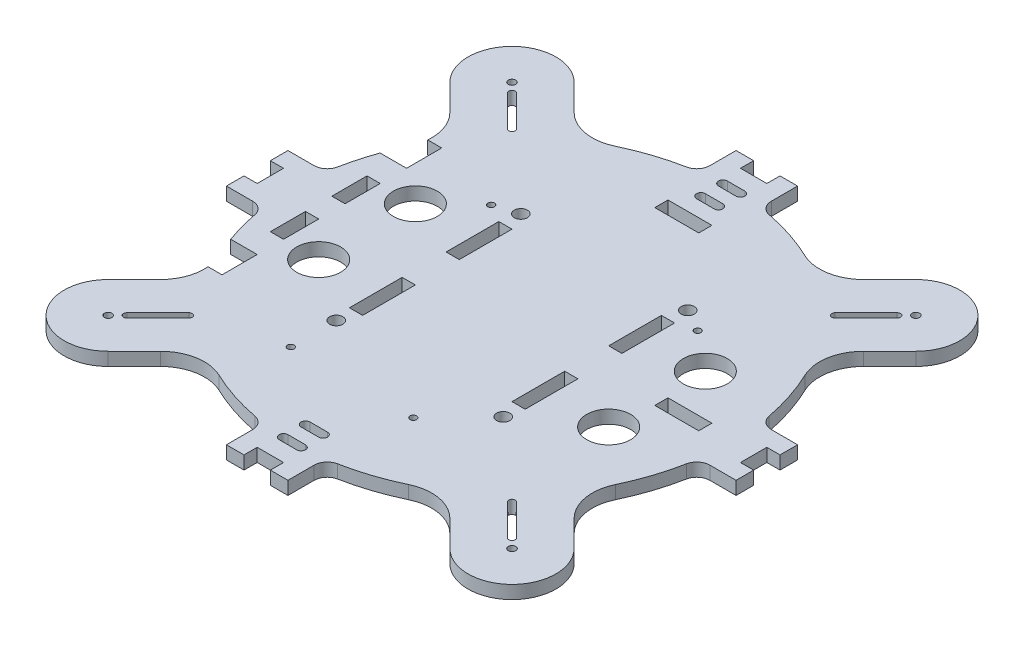
SolidWorks part; units mm, degrees
ref_plane "Plan de face" through (0, 0, 0) normal (0, 0, 1) x (1, 0, 0)
ref_plane "Plan de dessus" through (0, 0, 0) normal (0, 1, 0) x (1, 0, 0)
ref_plane "Plan de droite" through (0, 0, 0) normal (1, 0, 0) x (0, 0, -1)
sketch "Esquisse1" plane through (0, 0, 0) normal (0, 1, 0) x (1, 0, 0)
  line L0 (-45.9619, -45.9619) -> (0, 0) construction
  line L1 (0, 0) -> (-75, 0) construction
  line L2 (-45.9619, -45.9619) -> (-53.033, -53.033) construction
  line L3 (0, 0) -> (0, 75) construction
  line L4 (-38.8909, -53.033) -> (-27.5699, -41.7121)
  line L5 (-53.033, -38.8909) -> (-41.7121, -27.5699)
  line L6 (-38.8909, 53.033) -> (-27.5699, 41.7121)
  line L7 (-41.7121, 27.5699) -> (-53.033, 38.8909)
  line L8 (0, 0) -> (-45.9619, 45.9619) construction
  line L9 (0, 0) -> (45.9619, 45.9619) construction
  line L10 (0, 0) -> (45.9619, -45.9619) construction
  line L11 (27.5699, 41.7121) -> (38.8909, 53.033)
  line L12 (41.7121, 27.5699) -> (53.033, 38.8909)
  line L13 (27.5699, -41.7121) -> (38.8909, -53.033)
  line L14 (41.7121, -27.5699) -> (53.033, -38.8909)
  line L15 (-20, 17) -> (-17, 17)
  line L18 (-20, 17) -> (-20, 5)
  line L21 (-20, 5) -> (-17, 5)
  line L24 (-17, 17) -> (-17, 5)
  line L27 (-19, -21) -> (19, -21) construction
  line L28 (-19, -21) -> (-19, 21) construction
  line L29 (-19, 21) -> (19, 21) construction
  line L30 (19, -21) -> (19, 21) construction
  line L31 (-19, -21) -> (19, 21) construction
  line L32 (-19, 21) -> (19, -21) construction
  line L33 (20, 5) -> (17, 5)
  line L34 (17, 17) -> (17, 5)
  line L35 (20, 17) -> (17, 17)
  line L36 (20, 17) -> (20, 5)
  line L37 (-17, 5) -> (-17, -5) construction
  line L38 (17, -17) -> (20, -17)
  line L39 (-17, -5) -> (-20, -5)
  line L40 (-17, -5) -> (-17, -17)
  line L41 (-17, -17) -> (-20, -17)
  line L42 (-20, -5) -> (-20, -17)
  line L43 (20, -5) -> (20, -17)
  line L44 (17, -5) -> (20, -5)
  line L45 (17, -5) -> (17, -17)
  line L46 (-43.8406, -43.8406) -> (-36.7696, -36.7696) construction
  line L47 (-24.15, 19.4) -> (24.15, 19.4) construction
  line L48 (-24.15, 19.4) -> (-24.15, -31.4) construction
  line L49 (-24.15, -31.4) -> (24.15, -31.4) construction
  line L50 (24.15, 19.4) -> (24.15, -31.4) construction
  line L51 (33, -11) -> (-33, -11) construction
  line L52 (33, -11) -> (33, 11) construction
  line L53 (33, 11) -> (-33, 11) construction
  line L54 (-33, -11) -> (-33, 11) construction
  line L55 (33, -11) -> (-33, 11) construction
  line L56 (33, 11) -> (-33, -11) construction
  line L57 (-44.371, -43.3103) -> (-37.2999, -36.2392)
  line L58 (-43.3103, -44.371) -> (-36.2392, -37.2999)
  line L59 (-43.8406, 43.8406) -> (-36.7696, 36.7696) construction
  line L60 (-43.3103, 44.371) -> (-36.2392, 37.2999)
  line L61 (-44.371, 43.3103) -> (-37.2999, 36.2392)
  line L62 (-24.15, 0) -> (24.15, 0) construction
  line L63 (43.8406, 43.8406) -> (36.7696, 36.7696) construction
  line L64 (44.371, 43.3103) -> (37.2999, 36.2392)
  line L65 (43.3103, 44.371) -> (36.2392, 37.2999)
  line L66 (43.8406, -43.8406) -> (36.7696, -36.7696) construction
  line L67 (43.3103, -44.371) -> (36.2392, -37.2999)
  line L68 (44.371, -43.3103) -> (37.2999, -36.2392)
  line L69 (-2, -45) -> (2, -45) construction
  line L70 (-2, -44) -> (2, -44)
  line L71 (-2, -46) -> (2, -46)
  line L72 (-2, -50) -> (2, -50) construction
  line L73 (-2, -49) -> (2, -49)
  line L74 (-2, -51) -> (2, -51)
  line L75 (0, 0) -> (0, -75) construction
  line L76 (-7, -58) -> (-3, -58)
  line L77 (7, -58) -> (7, -49.5076)
  line L78 (-7, -58) -> (-7, -49.5076)
  line L79 (-3, -58) -> (-3, -55)
  line L80 (-3, -55) -> (3, -55)
  line L81 (3, -55) -> (3, -58)
  line L82 (3, -58) -> (7, -58)
  line L83 (-58, -7) -> (-49.5076, -7)
  line L84 (-58, -3) -> (-58, -7)
  line L85 (-55, -3) -> (-58, -3)
  line L86 (-55, 3) -> (-55, -3)
  line L87 (-58, 3) -> (-55, 3)
  line L88 (-58, 7) -> (-58, 3)
  line L89 (-58, 7) -> (-49.5076, 7)
  line L90 (-7, 58) -> (-7, 49.5076)
  line L91 (-3, 58) -> (-7, 58)
  line L92 (-3, 55) -> (-3, 58)
  line L93 (3, 55) -> (-3, 55)
  line L94 (3, 58) -> (3, 55)
  line L95 (7, 58) -> (3, 58)
  line L96 (7, 58) -> (7, 49.5076)
  line L97 (58, 7) -> (49.5076, 7)
  line L98 (58, 3) -> (58, 7)
  line L99 (55, 3) -> (58, 3)
  line L100 (55, -3) -> (55, 3)
  line L101 (58, -3) -> (55, -3)
  line L102 (58, -7) -> (58, -3)
  line L103 (58, -7) -> (49.5076, -7)
  line L104 (-2, 50) -> (2, 50) construction
  line L105 (-2, 49) -> (2, 49)
  line L106 (-2, 51) -> (2, 51)
  line L107 (-2, 45) -> (2, 45) construction
  line L108 (-2, 44) -> (2, 44)
  line L109 (-2, 46) -> (2, 46)
  line L110 (0, 0) -> (75, 0) construction
  line L111 (34, 1.5) -> (44, 1.5)
  line L112 (34, 1.5) -> (34, -1.5)
  line L113 (34, -1.5) -> (44, -1.5)
  line L114 (44, 1.5) -> (44, -1.5)
  line L116 (-5, 40.5) -> (5, 40.5)
  line L117 (-5, 40.5) -> (-5, 37.5)
  line L118 (-5, 37.5) -> (5, 37.5)
  line L119 (5, 40.5) -> (5, 37.5)
  circle A0 centre (0, 0) radius 75 construction
  circle A1 centre (-45.9619, -45.9619) radius 0.85
  circle A2 centre (-45.9619, 45.9619) radius 0.85
  circle A3 centre (45.9619, 45.9619) radius 0.85
  circle A4 centre (45.9619, -45.9619) radius 0.85
  arc A9 (-27.5699, -41.7121) -> (-7, -49.5076) centre (0, 0) ccw
  arc A10 (-53.033, -38.8909) -> (-38.8909, -53.033) centre (-45.9619, -45.9619) ccw
  arc A11 (38.8909, -53.033) -> (53.033, -38.8909) centre (45.9619, -45.9619) ccw
  arc A12 (53.033, 38.8909) -> (38.8909, 53.033) centre (45.9619, 45.9619) ccw
  arc A13 (-38.8909, 53.033) -> (-53.033, 38.8909) centre (-45.9619, 45.9619) ccw
  arc A14 (-41.7121, 27.5699) -> (-49.5076, 7) centre (0, 0) ccw
  arc A15 (27.5699, 41.7121) -> (7, 49.5076) centre (0, 0) ccw
  arc A16 (41.7121, -27.5699) -> (49.5076, -7) centre (0, 0) ccw
  circle A25 centre (-19, 21) radius 1.5
  circle A26 centre (19, 21) radius 1.5
  circle A27 centre (19, -21) radius 1.5
  circle A28 centre (-19, -21) radius 1.5
  circle A29 centre (24.15, 18.1) radius 0.75
  circle A30 centre (-24.15, 19.4) radius 0.75
  circle A31 centre (-18.95, -31.4) radius 0.75
  circle A32 centre (8.95, -31.4) radius 0.75
  circle A33 centre (-33, 11) radius 5
  circle A34 centre (33, 11) radius 5
  circle A35 centre (33, -11) radius 5
  circle A36 centre (-33, -11) radius 5
  arc A37 (-44.371, -43.3103) -> (-43.3103, -44.371) centre (-43.8406, -43.8406) ccw
  arc A38 (-36.2392, -37.2999) -> (-37.2999, -36.2392) centre (-36.7696, -36.7696) ccw
  arc A39 (-43.3103, 44.371) -> (-44.371, 43.3103) centre (-43.8406, 43.8406) ccw
  arc A40 (-37.2999, 36.2392) -> (-36.2392, 37.2999) centre (-36.7696, 36.7696) ccw
  arc A41 (44.371, 43.3103) -> (43.3103, 44.371) centre (43.8406, 43.8406) ccw
  arc A42 (36.2392, 37.2999) -> (37.2999, 36.2392) centre (36.7696, 36.7696) ccw
  arc A43 (43.3103, -44.371) -> (44.371, -43.3103) centre (43.8406, -43.8406) ccw
  arc A44 (37.2999, -36.2392) -> (36.2392, -37.2999) centre (36.7696, -36.7696) ccw
  arc A45 (-2, -44) -> (-2, -46) centre (-2, -45) ccw
  arc A46 (2, -46) -> (2, -44) centre (2, -45) ccw
  arc A47 (-2, -49) -> (-2, -51) centre (-2, -50) ccw
  arc A48 (2, -51) -> (2, -49) centre (2, -50) ccw
  arc A49 (7, -49.5076) -> (27.5699, -41.7121) centre (0, 0) ccw
  arc A50 (-49.5076, -7) -> (-41.7121, -27.5699) centre (0, 0) ccw
  arc A51 (49.5076, 7) -> (41.7121, 27.5699) centre (0, 0) ccw
  arc A52 (-7, 49.5076) -> (-27.5699, 41.7121) centre (0, 0) ccw
  arc A53 (-2, 49) -> (-2, 51) centre (-2, 50) cw
  arc A54 (2, 51) -> (2, 49) centre (2, 50) cw
  arc A55 (-2, 44) -> (-2, 46) centre (-2, 45) cw
  arc A56 (2, 46) -> (2, 44) centre (2, 45) cw
  point P15 (0, 0)
  point P23 (0, 0)
  point P54 (-17, 0)
  point P66 (-40.3051, -40.3051)
  point P70 (0, 0)
  point P73 (0, 0)
  point P89 (0, -45)
  point P92 (-40.3051, 40.3051)
  point P99 (40.3051, 40.3051)
  point P106 (40.3051, -40.3051)
  point P111 (0, 0)
  point P117 (0, -50)
  point P128 (0, -55)
  point P132 (34, 0)
  point P160 (0, 0)
  point P161 (0, 50)
  point P168 (0, 45)
  point P182 (0, 37.5)
  dimension "D2" = 1.7
  dimension "D7" = 38
  dimension "D6" = 150
  dimension "D12" = 34
  dimension "D9" = 3
  dimension "D13" = 19.4
  dimension "D25" = 1.5
  dimension "D19" = 50
  dimension "D22" = 10
  dimension "D24" = 0.75
  dimension "D29" = 1
  dimension "D3" = 10
  dimension "D4" = 45
  dimension "D10" = 3
  dimension "D11" = 12
  dimension "D8" = 42
  dimension "D14" = 17
  dimension "D15" = 50.8
  dimension "D16" = 48.3
  dimension "D17" = 5.2
  dimension "D18" = 1.3
  dimension "D20" = 22
  dimension "D21" = 66
  dimension "D23" = 3
  dimension "D26" = 10
  dimension "D27" = 4
  dimension "D28" = 4
  dimension "D30" = 45
  dimension "D31" = 27.9
  dimension "D32" = 5
  dimension "D33" = 14
  dimension "D34" = 58
  dimension "D35" = 3
  dimension "D36" = 6
  dimension "D38" = 10
  dimension "D39" = 3
  dimension "D40" = 34
  dimension "D41" = 37.5
  dimension "D42" = 10
  dimension "D43" = 3
  dimension "D5" = 4
  dimension "D37" = 4
extrude "Boss.-Extru.1" add sketch "Esquisse1" along normal blind 3
fillet "Congé1" radius 10 8 edges at (27.5699, 1.5, -41.7121) (41.7121, 1.5, 27.5699) (-27.5699, 1.5, 41.7121) (-41.7121, 1.5, -27.5699) (-27.5699, 1.5, -41.7121) (41.7121, 1.5, -27.5699) (27.5699, 1.5, 41.7121) (-41.7121, 1.5, 27.5699)
fillet "Congé2" radius 3 8 edges at (-7, 1.5, 49.5076) (7, 1.5, 49.5076) (49.5076, 1.5, 7) (49.5076, 1.5, -7) (7, 1.5, -49.5076) (-7, 1.5, -49.5076) (-49.5076, 1.5, -7) (-49.5076, 1.5, 7)
sketch "Esquisse4" plane through (0, 3, 0) normal (0, 1, 0) x (1, 0, 0)
  line L1 (-51, 25) -> (-41, 25)
  line L2 (-51, 25) -> (-51, 17)
  line L3 (-51, 17) -> (-41, 17)
  line L4 (-41, 25) -> (-41, 17)
  line L5 (-41, 11) -> (-44, 11)
  line L6 (-41, 11) -> (-41, 3)
  line L7 (-41, 3) -> (-44, 3)
  line L8 (-44, 11) -> (-44, 3)
  line L16 (0, 0) -> (-41, 0) construction
  line L17 (-41, 0) -> (-41, 3) construction
  line L18 (-51, -25) -> (-51, -17)
  line L19 (-51, -17) -> (-41, -17)
  line L20 (-41, -25) -> (-41, -17)
  line L21 (-51, -25) -> (-41, -25)
  line L22 (-41, -11) -> (-41, -3)
  line L23 (-41, -3) -> (-44, -3)
  line L24 (-44, -11) -> (-44, -3)
  line L25 (-41, -11) -> (-44, -11)
  dimension "D1" = 8
  dimension "D2" = 10
  dimension "D3" = 6
  dimension "D4" = 3
  dimension "D5" = 41
  dimension "D6" = 3
extrude "Enlèv. mat.-Extru.1" cut sketch "Esquisse4" against normal up to next
